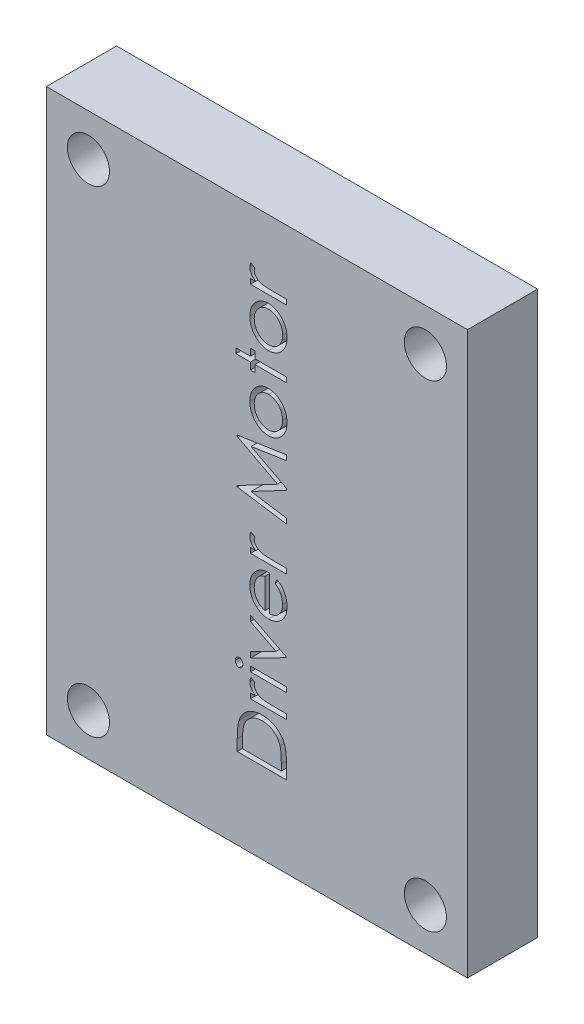
SolidWorks part; units mm, degrees
ref_plane "Plan de face" through (0, 0, 0) normal (0, 0, 1) x (1, 0, 0)
ref_plane "Plan de dessus" through (0, 0, 0) normal (0, 1, 0) x (1, 0, 0)
ref_plane "Plan de droite" through (0, 0, 0) normal (1, 0, 0) x (0, 0, -1)
sketch "Esquisse1" plane through (0, 0, 0) normal (0, 0, 1) x (1, 0, 0)
  line L1 (0, 0) -> (-30, 0)
  line L2 (0, 0) -> (0, 40)
  line L3 (0, 40) -> (-30, 40)
  line L4 (-30, 0) -> (-30, 40)
  dimension "D1" = 40
  dimension "D2" = 30
extrude "Extrusion1" add sketch "Esquisse1" along normal blind 5
sketch "Esquisse2" plane through (0, 0, 5) normal (0, 0, 1) x (1, 0, 0)
  line L0 (-12.9021, 2.3621) -> (-12.9021, 37.1717) construction
  text T0 "  Driver Motor" font "Century Gothic" height 3.5
extrude "Enlèv. mat.-Extru.1" cut sketch "Esquisse2" against normal blind 2
sketch "Esquisse3" plane through (0, 0, 0) normal (0, 0, 1) x (1, 0, 0)
  line L0 (-30, 40) -> (-30, 0) construction
  line L1 (0, 40) -> (-30, 40) construction
  line L2 (-27, 37) -> (-3, 37) construction
  line L3 (-3, 37) -> (-3, 3) construction
  line L4 (-3, 3) -> (-27, 3) construction
  line L5 (-27, 3) -> (-27, 37) construction
  circle A0 centre (-27, 37) radius 1.5
  circle A1 centre (-3, 37) radius 1.5
  circle A2 centre (-3, 3) radius 1.5
  circle A3 centre (-27, 3) radius 1.5
  dimension "D1" = 3
  dimension "D2" = 3
  dimension "D3" = 3
  dimension "D4" = 3
  dimension "D5" = 3
  dimension "D6" = 3
  dimension "D7" = 24
  dimension "D8" = 34
extrude "Enlèv. mat.-Extru.2" cut sketch "Esquisse3" along normal blind 8
